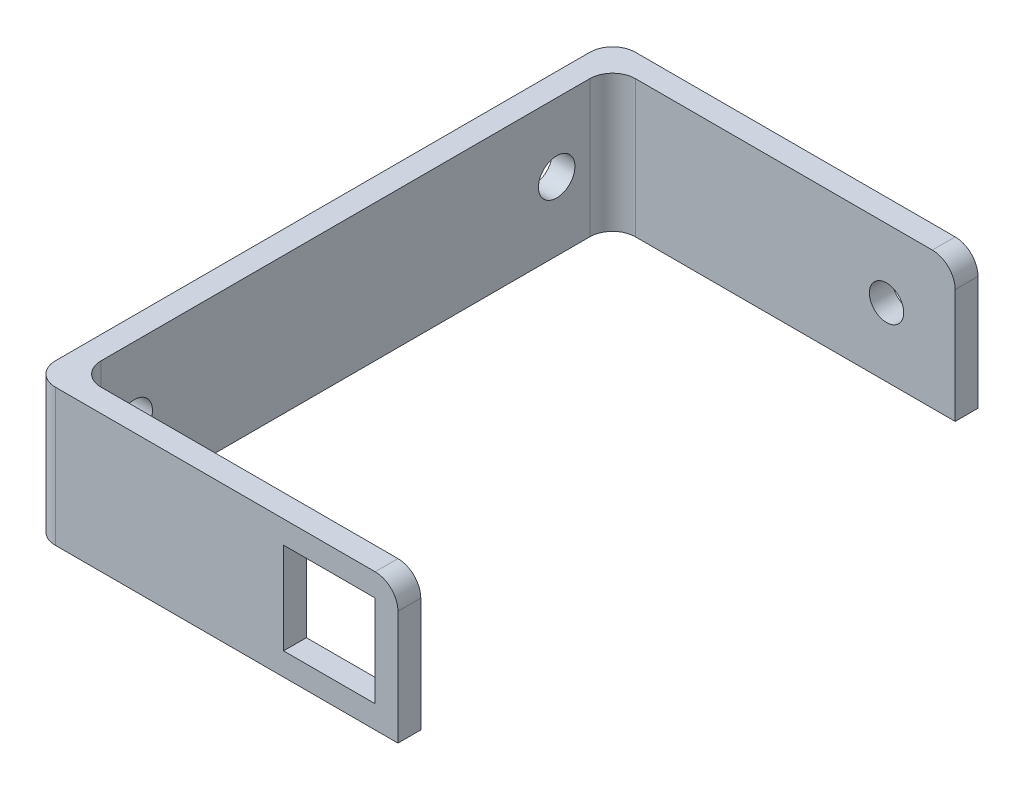
SolidWorks part; units mm, degrees
ref_plane "Front Plane" through (0, 0, 0) normal (0, 0, 1) x (1, 0, 0)
ref_plane "Top Plane" through (0, 0, 0) normal (0, 1, 0) x (1, 0, 0)
ref_plane "Right Plane" through (0, 0, 0) normal (1, 0, 0) x (0, 0, -1)
sketch "Sketch1" plane through (0, 0, 0) normal (0, 1, 0) x (1, 0, 0)
  line L0 (0, 0) -> (-32, 0)
  line L1 (-32, 0) -> (-32, 50.8)
  line L2 (-32, 50.8) -> (0, 50.8)
  line L3 (0, 50.8) -> (0, 48.8)
  line L4 (0, 48.8) -> (-30, 48.8)
  line L5 (-30, 48.8) -> (-30, 2)
  line L6 (-30, 2) -> (0, 2)
  line L7 (0, 2) -> (0, 0)
  dimension "D1" = 2
  dimension "D2" = 2
  dimension "D3" = 32
  dimension "D4" = 2
  dimension "D5" = 46.8
extrude "Boss-Extrude1" add sketch "Sketch1" along normal blind 12
sketch "Sketch3" plane through (0, 0, -50.8) normal (0, 0, -1) x (-1, 0, 0)
  line L0 (0, 6) -> (32, 6) construction
  line L1 (0, 12) -> (0, 0) construction
  line L2 (32, 12) -> (32, 0) construction
  circle A0 centre (6.01, 6) radius 1.505
  dimension "D2" = 3.01
  dimension "D1" = 6.01
extrude "Cut-Extrude2" cut sketch "Sketch3" against normal blind 4
sketch "Sketch5" plane through (-32, 0, 0) normal (-1, 0, 0) x (0, 0, 1)
  circle A0 centre (-43.9, 6) radius 1.6
  circle A1 centre (-6.9, 6) radius 1.6
extrude "Cut-Extrude3" cut sketch "Sketch5" against normal blind 4
sketch "Sketch6" plane through (0, 0, 0) normal (0, 0, 1) x (1, 0, 0)
  line L0 (-32, 6) -> (0, 6) construction
  line L1 (-32, 12) -> (-32, 0) construction
  line L2 (0, 12) -> (0, 0) construction
  line L4 (-10.02, 1.99) -> (-2, 1.99)
  line L5 (-10.02, 1.99) -> (-10.02, 10.01)
  line L6 (-10.02, 10.01) -> (-2, 10.01)
  line L7 (-2, 1.99) -> (-2, 10.01)
  line L8 (-10.02, 1.99) -> (-2, 10.01) construction
  line L9 (-10.02, 10.01) -> (-2, 1.99) construction
  point P6 (-6.01, 6)
  dimension "D1" = 8.02
  dimension "D2" = 8.02
  dimension "D3" = 6.01
extrude "Cut-Extrude4" cut sketch "Sketch6" against normal blind 2
fillet "Fillet1" radius 2 1 edges at (0, 12, -1)
fillet "Fillet2" radius 2 1 edges at (0, 12, -49.8)
fillet "Fillet3" radius 2 1 edges at (-30, 6, -2)
fillet "Fillet4" radius 2 1 edges at (-32, 6, 0)
fillet "Fillet5" radius 2 1 edges at (-30, 6, -48.8)
fillet "Fillet6" radius 2 1 edges at (-32, 6, -50.8)
equation "\"BoxCouplerHole\"=8.02"
equation "\"D1@Sketch6\"=\"BoxCouplerHole\""
equation "\"AxelOffset\"= ( \"BoxCouplerHole\" / 2 ) + 2mm"
equation "\"D3@Sketch6\"=\"AxelOffset\""
equation "\"D1@Sketch3\"=\"AxelOffset\""
